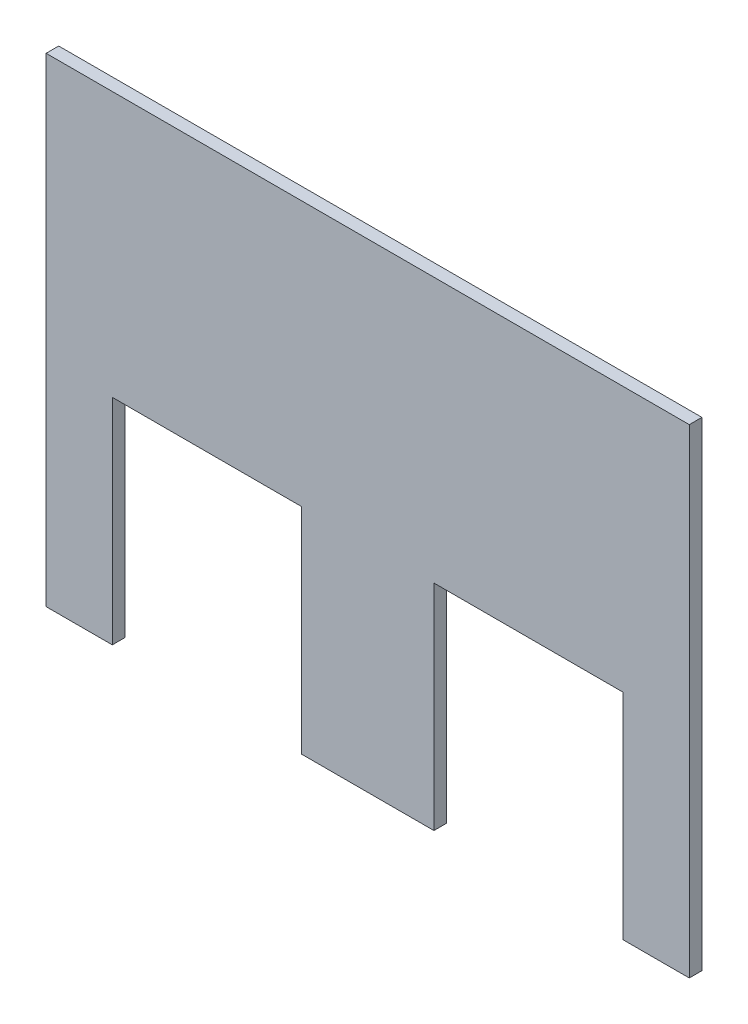
SolidWorks part; units mm, degrees
ref_plane "Front Plane" through (0, 0, 0) normal (0, 0, 1) x (1, 0, 0)
ref_plane "Top Plane" through (0, 0, 0) normal (0, 1, 0) x (1, 0, 0)
ref_plane "Right Plane" through (0, 0, 0) normal (1, 0, 0) x (0, 0, -1)
sketch "Sketch1" plane through (0, 0, 0) normal (0, 0, 1) x (1, 0, 0)
  line L1 (0, 380) -> (510, 380)
  line L2 (0, 380) -> (0, 0)
  line L3 (0, 0) -> (510, 0)
  line L4 (510, 380) -> (510, 0)
extrude "Boss-Extrude1" add sketch "Sketch1" along normal blind 10
sketch "Sketch2" plane through (0, 0, 10) normal (0, 0, 1) x (1, 0, 0)
  line L0 (255, 380) -> (255, 0)
  line L1 (510, 380) -> (0, 380) construction
  line L2 (0, 0) -> (510, 0) construction
  line L3 (255, 0) -> (0, 0) construction
  line L4 (127.5, 0) -> (127.5, 170)
  line L13 (202.5, 0) -> (202.5, 170)
  line L14 (52.5, 0) -> (52.5, 170)
  line L15 (52.5, 170) -> (202.5, 170)
  line L16 (202.5, 0) -> (52.5, 0)
  line L17 (307.5, 0) -> (457.5, 0)
  line L18 (457.5, 170) -> (307.5, 170)
  line L19 (457.5, 0) -> (457.5, 170)
  line L20 (307.5, 0) -> (307.5, 170)
  line L21 (382.5, 0) -> (382.5, 170)
  line M9 (0, 0) -> (510, 0)
  dimension "D1" = 170
  dimension "D2" = 75
  dimension "D3" = 75
extrude "Cut-Extrude1" cut sketch "Sketch2" against normal blind 10 contours L15 L14 L4 M9 | L15 L4 L13 M9 | L21 L18 L20 M9 | L21 L17 L19 L18
